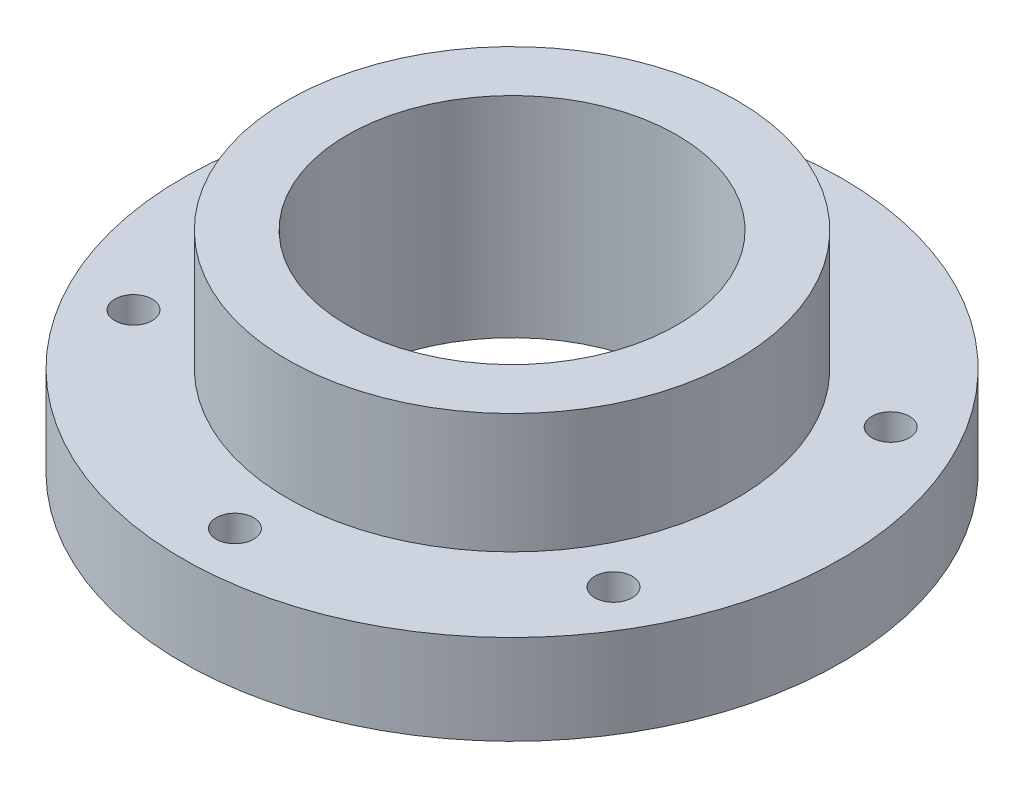
SolidWorks part; units mm, degrees
ref_plane "Front Plane" through (0, 0, 0) normal (0, 0, 1) x (1, 0, 0)
ref_plane "Top Plane" through (0, 0, 0) normal (0, 1, 0) x (1, 0, 0)
ref_plane "Right Plane" through (0, 0, 0) normal (1, 0, 0) x (0, 0, -1)
sketch "Sketch1" plane through (0, 0, 0) normal (0, 0, 1) x (1, 0, 0)
  line L0 (11, 0) -> (11, 14)
  line L1 (11, 14) -> (15, 14)
  line L2 (15, 14) -> (15, 6)
  line L3 (15, 6) -> (22, 6)
  line L4 (22, 6) -> (22, 0)
  line L5 (22, 0) -> (11, 0)
  line L6 (0, 0) -> (0, 9.5042) construction
  dimension "D1" = 11
  dimension "D2" = 15
  dimension "D3" = 6
  dimension "D4" = 7
  dimension "D5" = 14
revolve "Revolve1" add sketch "Sketch1" angle 360 about L6
sketch "Sketch2" plane through (0, 6, 0) normal (0, 1, 0) x (1, 0, 0)
  line L0 (0, 22) -> (0, 15) construction
  circle A0 centre (0, 18.5) radius 1.25
  circle A2 centre (0, 0) radius 22 construction
  circle A3 centre (0, 0) radius 15 construction
  circle A4 centre (16.0215, 9.25) radius 1.25
  circle A5 centre (16.0215, -9.25) radius 1.25
  circle A6 centre (0, -18.5) radius 1.25
  circle A7 centre (-16.0215, -9.25) radius 1.25
  circle A8 centre (-16.0215, 9.25) radius 1.25
  point P22 (0, 0)
  dimension "D1" = 2.5
  dimension "D2" = 6
extrude "Cut-Extrude1" cut sketch "Sketch2" against normal blind 10
